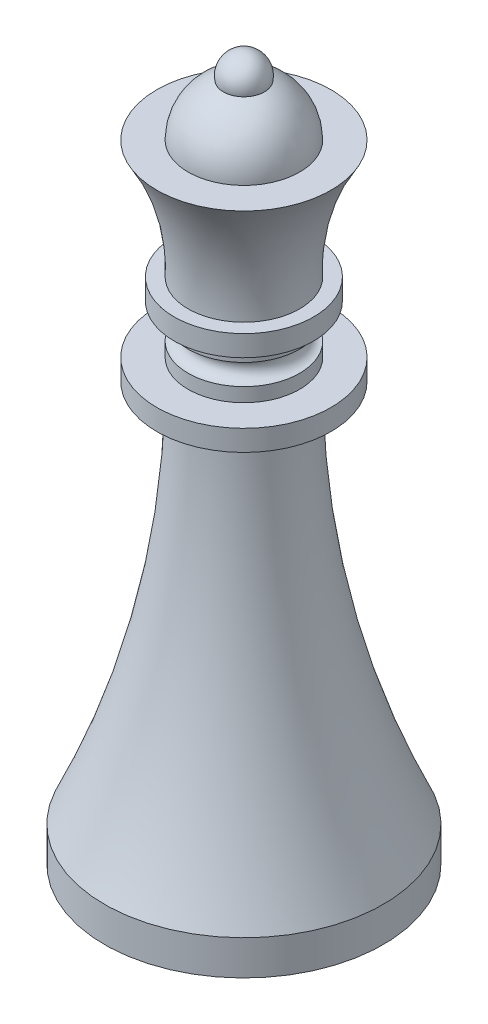
SolidWorks part; units mm, degrees
ref_plane "Front Plane" through (0, 0, 0) normal (0, 0, 1) x (1, 0, 0)
ref_plane "Top Plane" through (0, 0, 0) normal (0, 1, 0) x (1, 0, 0)
ref_plane "Right Plane" through (0, 0, 0) normal (1, 0, 0) x (0, 0, -1)
sketch "Sketch1" plane through (0, 0, 0) normal (0, 0, 1) x (1, 0, 0)
  line L0 (0, 50) -> (0, -70) construction
  line L1 (0, -60) -> (20, -60)
  line L2 (20, -60) -> (20, -55)
  line L3 (0, -60) -> (0, 41)
  line L4 (8, 0) -> (12.5, 0)
  line L5 (12.5, 0) -> (12.5, 3)
  line L6 (12.5, 3) -> (8, 3)
  line L10 (8, 10) -> (8, 8)
  line L11 (8, 5) -> (8, 3)
  line L13 (8, 13) -> (10, 13)
  line L14 (10, 13) -> (10, 10)
  line L15 (10, 10) -> (8, 10)
  line L16 (8, 30) -> (12.5, 30)
  arc A0 (8, 0) -> (20, -55) centre (140.0417, 0) ccw
  arc A1 (8, 8) -> (8, 5) centre (8, 6.5) ccw
  arc A2 (12.5, 30) -> (8, 13) centre (37.9776, 14.1604) ccw
  arc A3 (8, 30) -> (2.9468, 37.4375) centre (0, 30) ccw
  arc A4 (2.9468, 37.4375) -> (0, 41) centre (0, 38) ccw
  dimension "D12" = 30
  dimension "D1" = 50
  dimension "D2" = 70
  dimension "D4" = 20
  dimension "D5" = 5
  dimension "D8" = 3
  dimension "D10" = 12.5
revolve "Revolve1" add sketch "Sketch1" angle 360 about L0
fillet "Fillet1" radius 2 1 edges at (-8, 0, 0)
scale "缩放比例1" scale about origin uniform scaling yes scale factor 0.6
